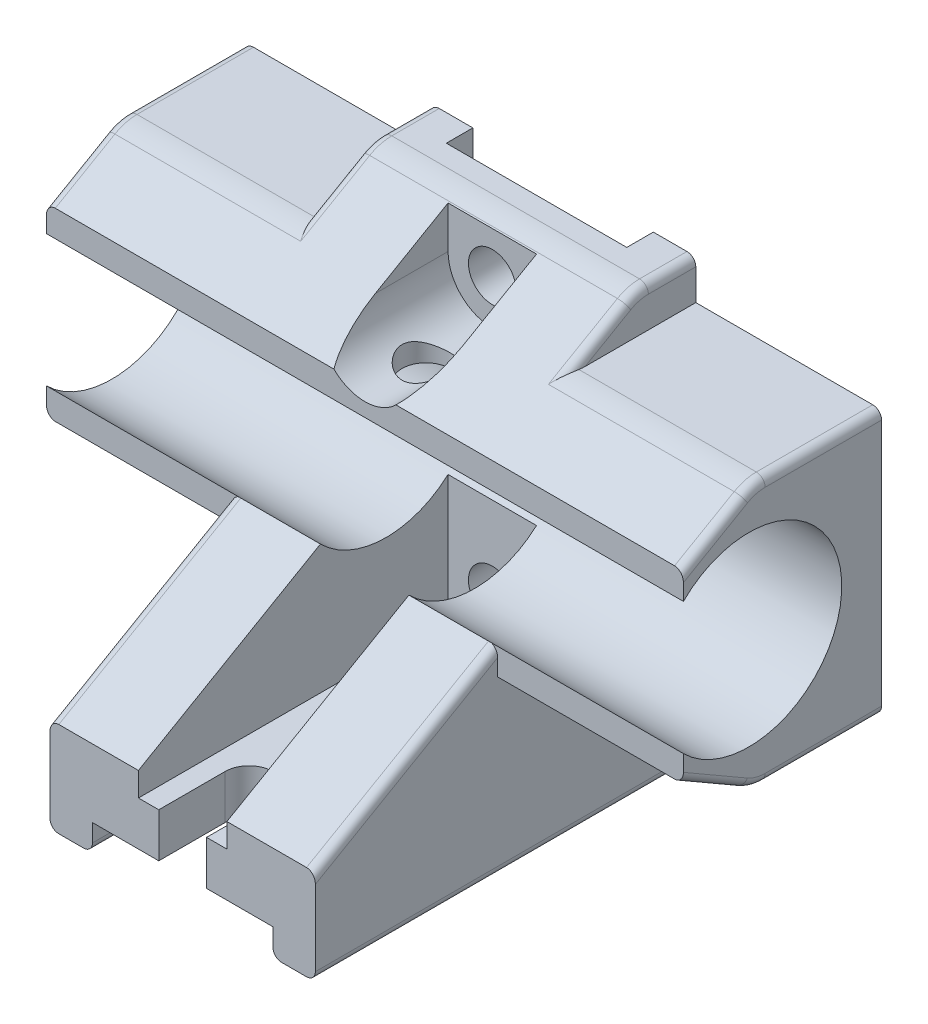
SolidWorks part; units mm, degrees
ref_plane "XY" through (0, 0, 0) normal (0, 0, 1) x (1, 0, 0)
ref_plane "XZ" through (0, 0, 0) normal (0, 1, 0) x (1, 0, 0)
ref_plane "YZ" through (0, 0, 0) normal (1, 0, 0) x (0, 0, -1)
sketch "Sketch2" plane through (0, 0, 0) normal (1, 0, 0) x (0, 0, -1)
  line L0 (0, 24.75) -> (-6.7, 24.75)
  line L1 (-6.7, 24.75) -> (-22.4, 15.6856)
  line L2 (-22.4, 15.6856) -> (-22.4, -2.1566)
  line L3 (-22.4, -2.1566) -> (-43, -14.05)
  line L4 (-43, -14.05) -> (-43, -24.75)
  line L5 (-43, -24.75) -> (0, -24.75)
  line L6 (0, -24.75) -> (0, 24.75)
  line L7 (-27.5732, 0) -> (27.2909, 0) construction
  dimension "D1" = 49.5
  dimension "D2" = 6.7
  dimension "D3" = 10.7
  dimension "D4" = 22.4
  dimension "D5" = 43
  dimension "D6" = 150
  dimension "D7" = 120
extrude "Boss-Extrude1" add sketch "Sketch2" along normal blind 15
sketch "Sketch3" plane through (15, 0, 0) normal (1, 0, 0) x (0, 0, -1)
  line L0 (-22.4, 15.6856) -> (-22.4, -5.1923)
  line L1 (-22.4, -5.1923) -> (-14.5, -9.7533)
  line L2 (-14.5, -9.7533) -> (0, -9.7533)
  line L3 (0, -24.75) -> (0, 24.75) construction
  line L4 (0, -9.7533) -> (0, 20.2467)
  line L5 (0, 20.2467) -> (-14.5, 20.2467)
  line L6 (-6.7, 24.75) -> (-22.4, 15.6856) construction
  line L7 (-14.5, 20.2467) -> (-22.4, 15.6856)
  line L8 (-22.4, 5.2467) -> (7.7029, 5.2467) construction
  dimension "D1" = 30
  dimension "D2" = 14.5
extrude "Boss-Extrude2" add sketch "Sketch3" along normal blind 21
sketch "Sketch4" plane through (0, 0, 43) normal (0, 0, 1) x (1, 0, 0)
  line L1 (0, -24.75) -> (10.2, -24.75)
  line L2 (0, -24.75) -> (0, -21.75)
  line L3 (0, -21.75) -> (10.2, -21.75)
  line L4 (10.2, -24.75) -> (10.2, -21.75)
  dimension "D1" = 3
  dimension "D2" = 10.2
extrude "Cut-Extrude1" cut sketch "Sketch4" against normal through all
sketch "Sketch9" plane through (36, 0, 0) normal (1, 0, 0) x (0, 0, -1)
  line L0 (-22.4, 15.6856) -> (-22.4, -5.1923) construction
  circle A0 centre (-15, 5.2467) radius 10.5
  point P4 (-22.4, 5.2467)
  dimension "D1" = 21
  dimension "D2" = 7.4
extrude "Cut-Extrude6" cut sketch "Sketch9" against normal through all
sketch "Sketch5" plane through (0, -21.75, 0) normal (0, -1, 0) x (1, 0, 0)
  line L0 (10.2, 0) -> (10.2, 43) construction
  line L1 (0, 0) -> (10.2, 0)
  line L2 (0, 0) -> (0, 3)
  line L3 (0, 3) -> (10.2, 3)
  line L4 (10.2, 0) -> (10.2, 3)
  dimension "D1" = 3
extrude "Cut-Extrude2" cut sketch "Sketch5" against normal through all
sketch "Sketch10" plane through (0, 0, 22.4) normal (0, 0, 1) x (1, 0, 0)
  line L1 (0, 12.6958) -> (5, 12.6958)
  line L2 (0, 12.6958) -> (0, 18.2796)
  line L3 (0, 18.2796) -> (5, 18.2796)
  line L4 (5, 12.6958) -> (5, 18.2796)
  dimension "D1" = 5
extrude "Boss-Extrude4" add sketch "Sketch10" against normal up to surface (19.4 mm away) up to face at (5.1, 1.5, 3)
sketch "Sketch11" plane through (5, 0, 0) normal (1, 0, 0) x (0, 0, -1)
  line L3 (-22.4, 15.6856) -> (-17.9071, 18.2796)
  line L4 (-17.9071, 18.2796) -> (-22.4, 18.2796)
  line L5 (-22.4, 18.2796) -> (-22.4, 15.6856)
  line L6 (-22.4, 15.6856) -> (-17.9071, 18.2796)
  line L7 (-17.9071, 18.2796) -> (-22.4, 18.2796)
  line L8 (-22.4, 18.2796) -> (-22.4, 15.6856)
  dimension "D1" = 0
extrude "Cut-Extrude7" cut sketch "Sketch11" against normal blind 5
sketch "Sketch6" plane through (0, 0, 22.4) normal (0, 0, 1) x (1, 0, 0)
  line L0 (0, 24.75) -> (0, 15.6856) construction
  line L1 (5, 19.25) -> (5, 24.75)
  line L2 (15, 24.75) -> (0, 24.75) construction
  line L3 (5, 24.75) -> (-5, 24.75)
  line L4 (-5, 24.75) -> (-5, 19.25)
  circle A0 centre (0, 19.25) radius 2.7
  arc A1 (-5, 19.25) -> (5, 19.25) centre (0, 19.25) ccw
  circle A2 centre (0, 19.25) radius 5 construction
  dimension "D1" = 5.4
  dimension "D2" = 19.25
  dimension "D3" = 2.3
extrude "Cut-Extrude3" cut sketch "Sketch6" against normal offset from surface (14.4 mm away) 5 up to face at (5.1, 1.5, 3)
sketch "Sketch7" plane through (0, 0, 22.4) normal (0, 0, 1) x (1, 0, 0)
  line L0 (0, 21.95) -> (0, 16.55)
  arc A0 (0, 16.55) -> (0, 21.95) centre (0, 19.25) ccw construction
  arc A1 (0, 16.55) -> (0, 21.95) centre (0, 19.25) ccw
extrude "Cut-Extrude4" cut sketch "Sketch7" against normal through all
sketch "Sketch8" plane through (0, 0, 43) normal (0, 0, 1) x (1, 0, 0)
  line L0 (0, -14.05) -> (0, -21.75) construction
  line L1 (0, -16.75) -> (5, -16.75)
  line L2 (0, -16.75) -> (0, 0)
  line L3 (0, 0) -> (5, 0)
  line L4 (5, -16.75) -> (5, 0)
  line L5 (15, -24.75) -> (10.2, -24.75) construction
  line L6 (0, 14.25) -> (0, 12.6958) construction
  dimension "D1" = 8
  dimension "D2" = 5
extrude "Cut-Extrude5" cut sketch "Sketch8" against normal up to surface (35 mm away) up to face at (2.2893, 19.8272, 8)
sketch "Sketch12" plane through (0, 0, 8) normal (0, 0, 1) x (1, 0, 0)
  line L0 (0, -16.75) -> (0, -2.5796) construction
  line L1 (15, -24.75) -> (10.2, -24.75) construction
  circle A0 centre (0, -11.75) radius 2.7
  dimension "D1" = 13
  dimension "D2" = 5.4
extrude "Cut-Extrude8" cut sketch "Sketch12" against normal blind 5
sketch "Sketch13" plane through (0, 24.75, 0) normal (0, 1, 0) x (1, 0, 0)
  line L0 (0, -22.4) -> (0, -8) construction
  line L1 (0, -8) -> (0, -43) construction
  line L2 (2.7, -35.5) -> (2.7, -43)
  line L3 (0, -43) -> (5, -43) construction
  line L4 (2.7, -43) -> (-2.7, -43)
  line L5 (-2.7, -43) -> (-2.7, -35.5)
  circle A0 centre (0, -15.5) radius 2.7
  arc A1 (2.7, -35.5) -> (-2.7, -35.5) centre (0, -35.5) ccw
  dimension "D1" = 35.5
  dimension "D2" = 2.7
  dimension "D3" = 5.4
  dimension "D4" = 15.5
extrude "Cut-Extrude9" cut sketch "Sketch13" against normal through all
fillet "Fillet1" radius 5 3 edges at (25.5, -9.7533, 14.5) (7.5, 24.75, 6.7)
fillet "Fillet2" radius 1 12 edges at (15, 24.75, 2.6801) (15, 24.5796, 6.6543) (36, 20.2467, 6.5801) (36, 20.0763, 14.4543) (36, -9.7533, 6.5801) (36, -9.583, 14.4543) (36, 17.6312, 19.0301) (36, -7.1379, 19.0301) (10.2, -24.75, 21.5) (15, -24.75, 21.5)
mirror "Mirror1" about plane through (0, 0, 0) normal (1, 0, 0) of bodies 130
